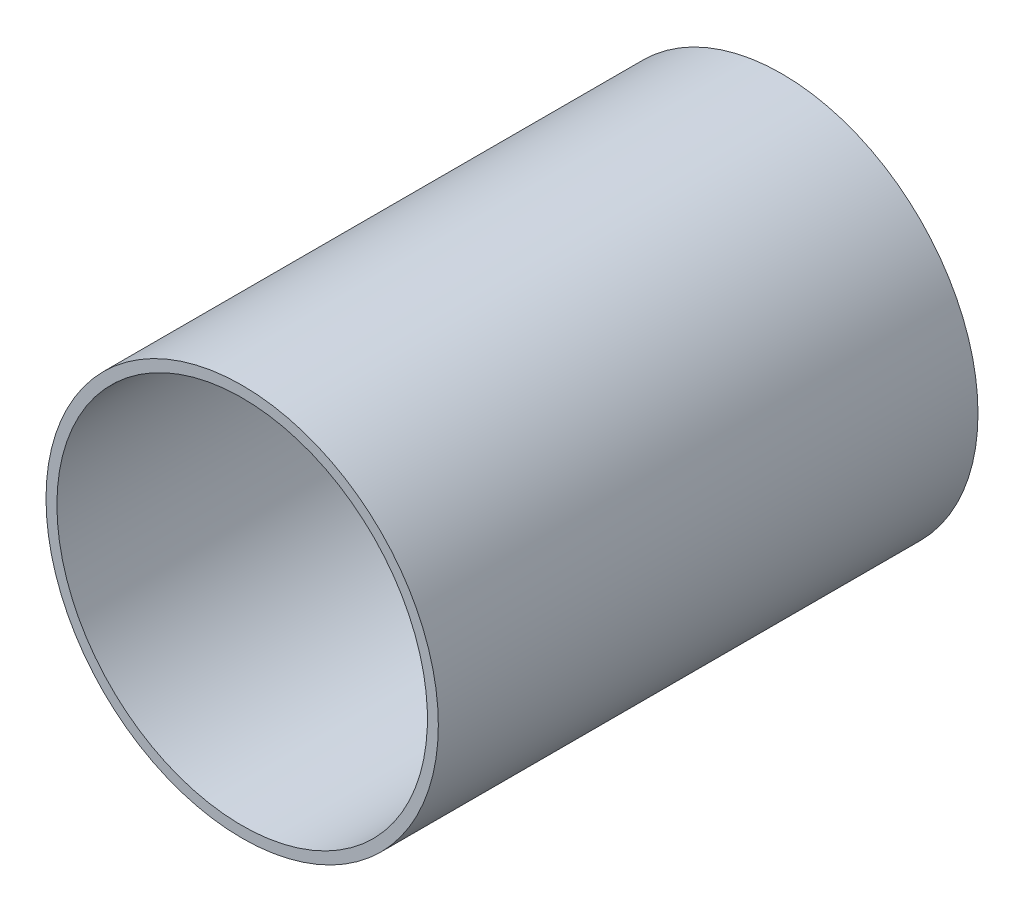
SolidWorks part; units mm, degrees
ref_plane "Front Plane" through (0, 0, 0) normal (0, 0, 1) x (1, 0, 0)
ref_plane "Top Plane" through (0, 0, 0) normal (0, 1, 0) x (1, 0, 0)
ref_plane "Right Plane" through (0, 0, 0) normal (1, 0, 0) x (0, 0, -1)
sketch "Sketch1" plane through (0, 0, 0) normal (0, 0, 1) x (1, 0, 0)
  circle A0 centre (0, 0) radius 53.975 construction
  circle A1 centre (0, 0) radius 57.15 construction
  point P4 (53.975, 0)
  point P5 (57.15, 0)
  dimension "ID" = 107.95
  dimension "OD" = 114.3
  dimension "Wall Thickness" = 3.175
sketch "Sketch2" plane through (0, 0, 0) normal (1, 0, 0) x (0, 0, -1)
  line L0 (-152.4, 0) -> (152.4, 0) construction
  line L1 (0, -57.15) -> (0, 57.15) construction
  line L2 (0, 57.15) -> (0, -57.15) construction
  point P0 (-23.8125, 0)
  point P4 (0, 0)
  point P8 (0, 0)
  point P13 (23.8125, 0)
  dimension "Length" = 304.8
  dimension "D1" = 128.5875
sketch "Sketch3" plane through (0, 0, 0) normal (0, 0, 1) x (1, 0, 0)
  circle A0 centre (0, 0) radius 53.975 construction
  circle A1 centre (0, 0) radius 57.15 construction
  circle A2 centre (0, 0) radius 53.975
  circle A3 centre (0, 0) radius 57.15
extrude "Boss-Extrude1" add sketch "Sketch3" along normal up to vertex (152.4 mm away) and the other way up to vertex (152.4 mm away) up to point (0, 0, 152.4) other way up to point (0, 0, -152.4)
sketch "Sketch5" plane through (0, 0, 152.4) normal (0, 0, 1) x (1, 0, 0)
  circle A0 centre (0, 0) radius 72.4773
  dimension "D1" = 144.9547
extrude "Cut-Extrude1" cut sketch "Sketch5" against normal blind 147.574
equation "\"D1@Sketch2\"=\"OD@Sketch1\"*1.125"
